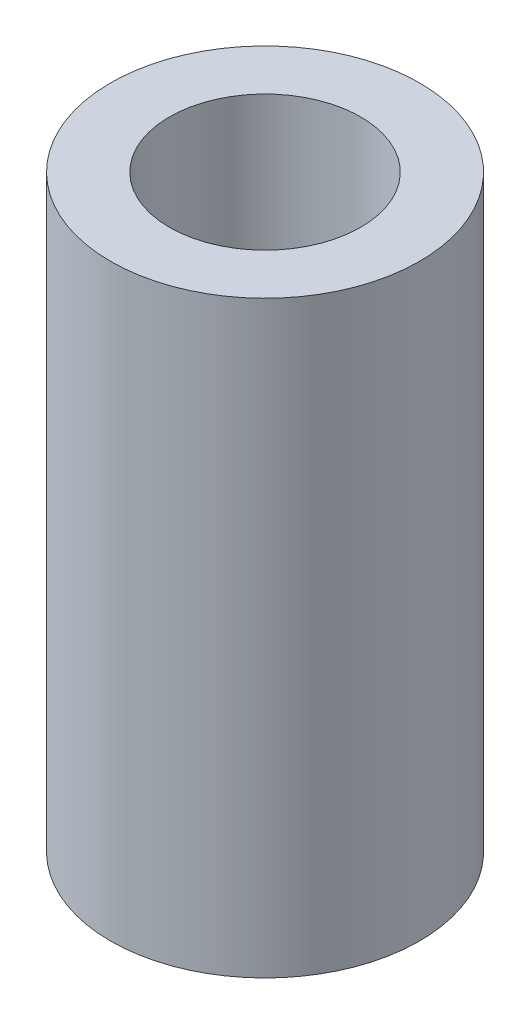
SolidWorks part; units mm, degrees
ref_plane "前视基准面" through (0, 0, 0) normal (0, 0, 1) x (1, 0, 0)
ref_plane "上视基准面" through (0, 0, 0) normal (0, 1, 0) x (1, 0, 0)
ref_plane "右视基准面" through (0, 0, 0) normal (1, 0, 0) x (0, 0, -1)
other "Configuration Table"
sketch "草图1" plane through (0, 0, 0) normal (0, 1, 0) x (1, 0, 0)
  circle A0 centre (0, -0.104) radius 3.25
  circle A1 centre (0, -0.104) radius 5.25
  dimension "D1" = 6.5
  dimension "D2" = 2
extrude "凸台-拉伸1" add sketch "草图1" along normal blind 20
